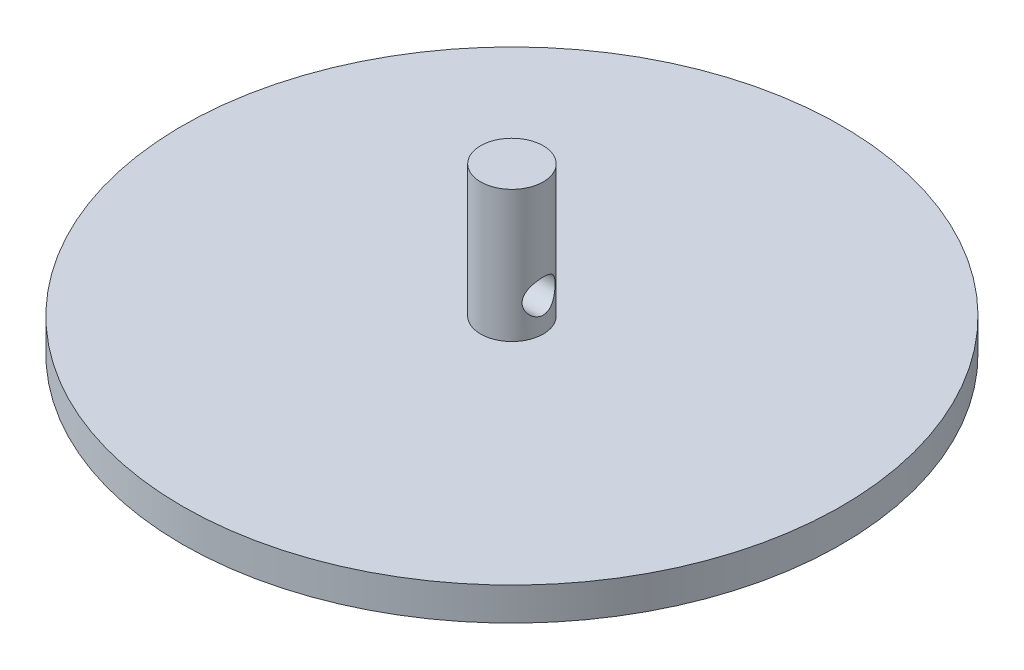
SolidWorks part; units mm, degrees
ref_plane "Front Plane" through (0, 0, 0) normal (0, 0, 1) x (1, 0, 0)
ref_plane "Top Plane" through (0, 0, 0) normal (0, 1, 0) x (1, 0, 0)
ref_plane "Right Plane" through (0, 0, 0) normal (1, 0, 0) x (0, 0, -1)
sketch "Sketch1" plane through (0, 0, 0) normal (0, 1, 0) x (1, 0, 0)
  circle A0 centre (0, 0) radius 50
  dimension "D1" = 100
extrude "Boss-Extrude1" add sketch "Sketch1" along normal blind 5
sketch "Sketch2" plane through (0, 5, 0) normal (0, 1, 0) x (1, 0, 0)
  circle A0 centre (0, 0) radius 4.75
  dimension "D1" = 9.5
extrude "Boss-Extrude2" add sketch "Sketch2" along normal blind 20
ref_plane "Plane1" through (4.75, 0, 0) normal (1, 0, 0) x (0, 0, -1)
sketch "Sketch3" plane through (4.75, 0, 0) normal (1, 0, 0) x (0, 0, -1)
  line L0 (0, 13.75) -> (0, -13.75) construction
  line L1 (4.75, 5) -> (-4.75, 5) construction
  circle A0 centre (0, 10) radius 2.5
  dimension "D1" = 5
  dimension "D2" = 5
extrude "Cut-Extrude1" cut sketch "Sketch3" against normal up to next
sketch "Sketch4" plane through (0, 0, 0) normal (1, 0, 0) x (0, 0, -1)
  line L0 (-50, 0) -> (50, 0) construction
  line L1 (55, 0) -> (-55, 0) construction
  line L2 (-50, 0) -> (50, 0)
  arc A0 (-50, 0) -> (50, 0) centre (0, -406.0553) cw
